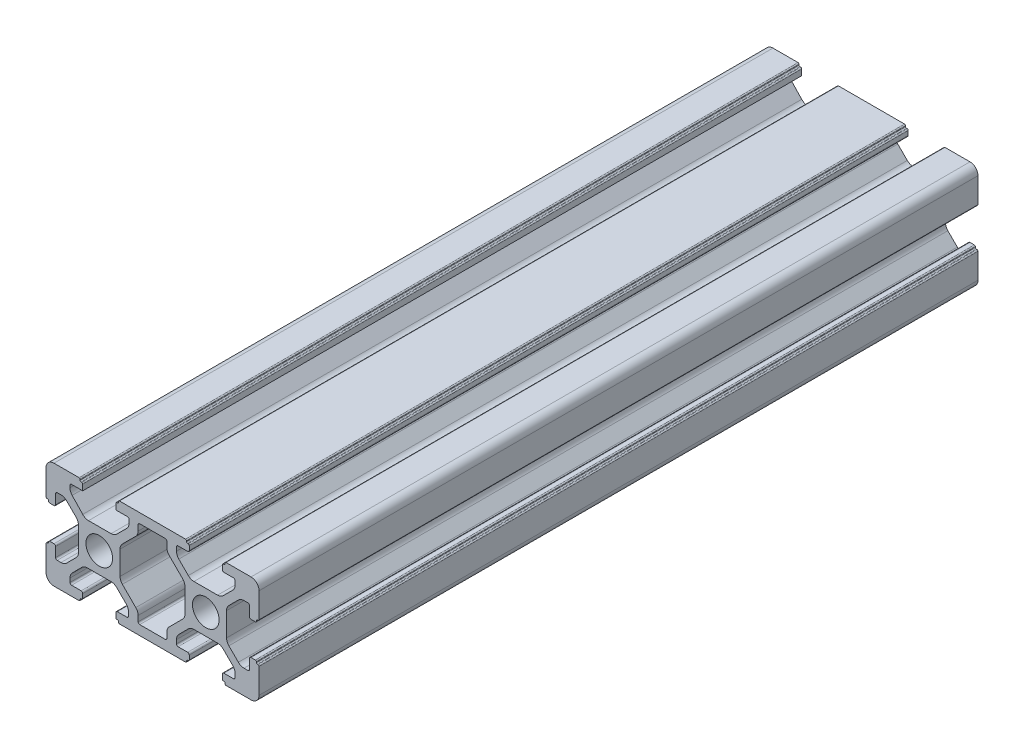
SolidWorks part; units mm, degrees
material "6063-O"
ref_plane "Front Plane" through (0, 0, 0) normal (0, 0, 1) x (1, 0, 0)
ref_plane "Top Plane" through (0, 0, 0) normal (0, 1, 0) x (1, 0, 0)
ref_plane "Right Plane" through (0, 0, 0) normal (1, 0, 0) x (0, 0, -1)
sketch "Sketch1" plane through (0, 0, 0) normal (0, 0, 1) x (1, 0, 0)
  line L0 (1.5, 0) -> (6.2, 0)
  line L1 (40, 1.5) -> (40, 6.2)
  line L2 (38.5, 20) -> (33.8, 20)
  line L3 (0, 18.5) -> (0, 13.8)
  line L4 (17.6, 1.8) -> (22.4, 1.8)
  line L5 (32.218, 13.9) -> (27.782, 13.9)
  line L6 (26.1, 12.218) -> (26.1, 7.782)
  line L7 (17.6, 18.2) -> (22.4, 18.2)
  line L8 (12.218, 13.9) -> (7.9864, 13.9)
  line L9 (6.1, 12.218) -> (6.1, 7.782)
  line L10 (7.782, 6.1) -> (12.218, 6.1)
  line L11 (13.9, 7.782) -> (13.9, 12.218)
  line L12 (27.782, 6.1) -> (32.218, 6.1)
  line L13 (33.9, 7.782) -> (33.9, 12.218)
  line L14 (26.7213, 14.3393) -> (24.9393, 16.1213)
  line L15 (33.2787, 14.3393) -> (35.0607, 16.1213)
  line L16 (34.3393, 13.2787) -> (36.1213, 15.0607)
  line L17 (25.6607, 6.7213) -> (23.1393, 4.2)
  line L18 (15.2, 1.8) -> (13.4, 1.8)
  line L19 (26.7213, 5.6607) -> (24.9393, 3.8787)
  line L20 (24.8, 1.8) -> (26.6, 1.8)
  line L21 (15.3, 18.2) -> (13.1, 18.2)
  line L22 (13.2787, 14.3393) -> (15.1607, 16.2213)
  line L23 (14.3393, 13.2787) -> (16.8607, 15.8)
  line L24 (5.6607, 6.7213) -> (3.8787, 4.9393)
  line L25 (6.7213, 5.6607) -> (4.9393, 3.8787)
  line L26 (6.897, 14.3689) -> (4.9106, 16.4674)
  line L27 (5.6607, 13.2787) -> (3.8787, 15.0607)
  line L28 (14.3393, 6.7213) -> (16.8607, 4.2)
  line L29 (13.2787, 5.6607) -> (15.0607, 3.8787)
  line L30 (24.8, 18.2) -> (26.6, 18.2)
  line L31 (25.6607, 13.2787) -> (23.1393, 15.8)
  line L32 (34.3393, 6.7213) -> (36.1213, 4.9393)
  line L33 (33.2787, 5.6607) -> (35.0607, 3.8787)
  line L34 (1.8, 15.2) -> (1.8, 13.4)
  line L35 (24.5, 2.1) -> (24.5, 2.818)
  line L36 (4.5, 2.1) -> (4.5, 2.818)
  line L37 (2.818, 4.5) -> (2.1, 4.5)
  line L38 (4.5, 17.9) -> (4.5, 17.4986)
  line L39 (2.818, 15.5) -> (2.1, 15.5)
  line L40 (15.6, 17.9) -> (15.6, 17.282)
  line L41 (15.5, 2.818) -> (15.5, 2.1)
  line L42 (38.2, 15.2) -> (38.2, 13.4)
  line L43 (35.5, 2.818) -> (35.5, 2.1)
  line L44 (37.182, 4.5) -> (37.9, 4.5)
  line L45 (35.5, 17.182) -> (35.5, 17.9)
  line L46 (37.182, 15.5) -> (37.9, 15.5)
  line L47 (17.3, 2.1) -> (17.3, 3.1393)
  line L48 (22.7, 2.1) -> (22.7, 3.1393)
  line L49 (17.3, 17.9) -> (17.3, 16.8607)
  line L50 (22.7, 17.9) -> (22.7, 16.8607)
  line L51 (24.5, 17.9) -> (24.5, 17.182)
  line L52 (6.9, 19.3) -> (6.9, 18.2)
  line L53 (13.1, 19.3) -> (13.1, 18.2)
  line L54 (6.9, 1.5) -> (6.9, 0.7)
  line L55 (13.1, 1.5) -> (13.1, 0.7)
  line L56 (13.8, 0) -> (26.2, 0)
  line L57 (6.6, 1.8) -> (4.8, 1.8)
  line L58 (6.9, 18.2) -> (4.8, 18.2)
  line L59 (6.2, 20) -> (1.5, 20)
  line L60 (39.3, 6.9) -> (38.5, 6.9)
  line L61 (39.3, 13.1) -> (38.5, 13.1)
  line L62 (1.5, 13.1) -> (0.7, 13.1)
  line L63 (1.5, 6.9) -> (0.7, 6.9)
  line L64 (0, 6.2) -> (0, 1.5)
  line L65 (1.8, 6.6) -> (1.8, 4.8)
  line L66 (38.2, 6.6) -> (38.2, 4.8)
  line L67 (40, 13.8) -> (40, 18.5)
  line L68 (33.1, 19.3) -> (33.1, 18.5)
  line L69 (26.9, 19.3) -> (26.9, 18.5)
  line L70 (26.9, 1.5) -> (26.9, 0.7)
  line L71 (33.1, 1.5) -> (33.1, 0.7)
  line L72 (33.8, 0) -> (38.5, 0)
  line L73 (33.4, 1.8) -> (35.2, 1.8)
  line L74 (26.2, 20) -> (13.8, 20)
  line L75 (33.4, 18.2) -> (35.2, 18.2)
  line L76 (6.7, 0.5) -> (6.6, 0.5)
  line L77 (6.4, 0.3) -> (6.4, 0.2)
  line L78 (13.3, 0.5) -> (13.4, 0.5)
  line L79 (13.6, 0.3) -> (13.6, 0.2)
  line L80 (26.7, 0.5) -> (26.6, 0.5)
  line L81 (26.4, 0.3) -> (26.4, 0.2)
  line L82 (33.3, 0.5) -> (33.4, 0.5)
  line L83 (33.6, 0.3) -> (33.6, 0.2)
  line L85 (6.4, 19.8) -> (6.4, 19.7)
  line L86 (6.6, 19.5) -> (6.7, 19.5)
  line L87 (13.6, 19.8) -> (13.6, 19.7)
  line L88 (13.4, 19.5) -> (13.3, 19.5)
  line L89 (26.4, 19.8) -> (26.4, 19.7)
  line L90 (26.6, 19.5) -> (26.7, 19.5)
  line L91 (33.6, 19.8) -> (33.6, 19.7)
  line L92 (33.4, 19.5) -> (33.3, 19.5)
  line L93 (0.5, 13.3) -> (0.5, 13.4)
  line L94 (0.3, 13.6) -> (0.2, 13.6)
  line L95 (0.5, 6.7) -> (0.5, 6.6)
  line L96 (0.3, 6.4) -> (0.2, 6.4)
  line L97 (39.5, 13.3) -> (39.5, 13.4)
  line L98 (39.7, 13.6) -> (39.8, 13.6)
  line L99 (39.5, 6.7) -> (39.5, 6.6)
  line L100 (39.7, 6.4) -> (39.8, 6.4)
  circle A0 centre (10, 10) radius 2.5
  circle A1 centre (30, 10) radius 2.5
  arc A2 (38.5, 0) -> (40, 1.5) centre (38.5, 1.5) ccw
  arc A3 (40, 18.5) -> (38.5, 20) centre (38.5, 18.5) ccw
  arc A4 (1.5, 0) -> (0, 1.5) centre (1.5, 1.5) cw
  arc A5 (1.5, 20) -> (0, 18.5) centre (1.5, 18.5) ccw
  arc A6 (26.7213, 5.6607) -> (27.782, 6.1) centre (27.782, 4.6) cw
  arc A7 (32.218, 6.1) -> (33.2787, 5.6607) centre (32.218, 4.6) cw
  arc A8 (33.9, 7.782) -> (34.3393, 6.7213) centre (35.4, 7.782) ccw
  arc A9 (33.2787, 14.3393) -> (32.218, 13.9) centre (32.218, 15.4) cw
  arc A10 (14.3393, 6.7213) -> (13.9, 7.782) centre (15.4, 7.782) cw
  arc A11 (14.3393, 13.2787) -> (13.9, 12.218) centre (15.4, 12.218) ccw
  arc A12 (25.6607, 6.7213) -> (26.1, 7.782) centre (24.6, 7.782) ccw
  arc A13 (26.1, 12.218) -> (25.6607, 13.2787) centre (24.6, 12.218) ccw
  arc A14 (27.782, 13.9) -> (26.7213, 14.3393) centre (27.782, 15.4) cw
  arc A15 (5.6607, 13.2787) -> (6.1, 12.218) centre (4.6, 12.218) cw
  arc A16 (5.6607, 6.7213) -> (6.1, 7.782) centre (4.6, 7.782) ccw
  arc A17 (13.2787, 5.6607) -> (12.218, 6.1) centre (12.218, 4.6) ccw
  arc A18 (6.7213, 5.6607) -> (7.782, 6.1) centre (7.782, 4.6) cw
  arc A19 (13.2787, 14.3393) -> (12.218, 13.9) centre (12.218, 15.4) cw
  arc A20 (6.897, 14.3689) -> (7.9864, 13.9) centre (7.9864, 15.4) ccw
  arc A21 (36.1213, 4.9393) -> (37.182, 4.5) centre (37.182, 6) ccw
  arc A22 (36.1213, 15.0607) -> (37.182, 15.5) centre (37.182, 14) cw
  arc A23 (35.0607, 16.1213) -> (35.5, 17.182) centre (34, 17.182) ccw
  arc A24 (24.5, 17.182) -> (24.9393, 16.1213) centre (26, 17.182) ccw
  arc A25 (22.7, 16.8607) -> (23.1393, 15.8) centre (24.2, 16.8607) ccw
  arc A26 (17.3, 16.8607) -> (16.8607, 15.8) centre (15.8, 16.8607) cw
  arc A27 (4.9106, 16.4674) -> (4.5, 17.4986) centre (6, 17.4986) cw
  arc A28 (15.6, 17.282) -> (15.1607, 16.2213) centre (14.1, 17.282) cw
  arc A29 (3.8787, 15.0607) -> (2.818, 15.5) centre (2.818, 14) ccw
  arc A30 (3.8787, 4.9393) -> (2.818, 4.5) centre (2.818, 6) cw
  arc A31 (4.9393, 3.8787) -> (4.5, 2.818) centre (6, 2.818) ccw
  arc A32 (35.0607, 3.8787) -> (35.5, 2.818) centre (34, 2.818) cw
  arc A33 (24.9393, 3.8787) -> (24.5, 2.818) centre (26, 2.818) ccw
  arc A34 (22.7, 3.1393) -> (23.1393, 4.2) centre (24.2, 3.1393) cw
  arc A35 (17.3, 3.1393) -> (16.8607, 4.2) centre (15.8, 3.1393) ccw
  arc A36 (15.5, 2.818) -> (15.0607, 3.8787) centre (14, 2.818) ccw
  arc A37 (1.8, 6.6) -> (1.5, 6.9) centre (1.5, 6.6) ccw
  arc A38 (1.8, 13.4) -> (1.5, 13.1) centre (1.5, 13.4) cw
  arc A39 (17.6, 18.2) -> (17.3, 17.9) centre (17.6, 17.9) ccw
  arc A40 (22.4, 1.8) -> (22.7, 2.1) centre (22.4, 2.1) ccw
  arc A41 (17.6, 1.8) -> (17.3, 2.1) centre (17.6, 2.1) cw
  arc A42 (15.2, 1.8) -> (15.5, 2.1) centre (15.2, 2.1) ccw
  arc A43 (6.6, 1.8) -> (6.9, 1.5) centre (6.6, 1.5) cw
  arc A44 (13.4, 1.8) -> (13.1, 1.5) centre (13.4, 1.5) ccw
  arc A45 (24.8, 1.8) -> (24.5, 2.1) centre (24.8, 2.1) cw
  arc A46 (35.2, 1.8) -> (35.5, 2.1) centre (35.2, 2.1) ccw
  arc A47 (26.6, 1.8) -> (26.9, 1.5) centre (26.6, 1.5) cw
  arc A48 (33.4, 1.8) -> (33.1, 1.5) centre (33.4, 1.5) ccw
  arc A49 (26.9, 18.5) -> (26.6, 18.2) centre (26.6, 18.5) cw
  arc A50 (33.1, 18.5) -> (33.4, 18.2) centre (33.4, 18.5) ccw
  arc A51 (37.9, 4.5) -> (38.2, 4.8) centre (37.9, 4.8) ccw
  arc A52 (38.5, 13.1) -> (38.2, 13.4) centre (38.5, 13.4) cw
  arc A53 (38.5, 6.9) -> (38.2, 6.6) centre (38.5, 6.6) ccw
  arc A54 (38.2, 15.2) -> (37.9, 15.5) centre (37.9, 15.2) ccw
  arc A55 (35.2, 18.2) -> (35.5, 17.9) centre (35.2, 17.9) cw
  arc A56 (24.8, 18.2) -> (24.5, 17.9) centre (24.8, 17.9) ccw
  arc A57 (22.4, 18.2) -> (22.7, 17.9) centre (22.4, 17.9) cw
  arc A58 (15.3, 18.2) -> (15.6, 17.9) centre (15.3, 17.9) cw
  arc A59 (4.5, 17.9) -> (4.8, 18.2) centre (4.8, 17.9) cw
  arc A60 (1.8, 15.2) -> (2.1, 15.5) centre (2.1, 15.2) cw
  arc A61 (1.8, 4.8) -> (2.1, 4.5) centre (2.1, 4.8) ccw
  arc A62 (4.5, 2.1) -> (4.8, 1.8) centre (4.8, 2.1) ccw
  arc A63 (34.3393, 13.2787) -> (33.9, 12.218) centre (35.4, 12.218) ccw
  arc A64 (6.4, 0.2) -> (6.2, 0) centre (6.2, 0.2) cw
  arc A65 (6.6, 0.5) -> (6.4, 0.3) centre (6.6, 0.3) ccw
  arc A66 (6.7, 0.5) -> (6.9, 0.7) centre (6.7, 0.7) ccw
  arc A67 (13.6, 0.2) -> (13.8, 0) centre (13.8, 0.2) ccw
  arc A68 (13.4, 0.5) -> (13.6, 0.3) centre (13.4, 0.3) cw
  arc A69 (13.3, 0.5) -> (13.1, 0.7) centre (13.3, 0.7) cw
  arc A70 (26.4, 0.2) -> (26.2, 0) centre (26.2, 0.2) cw
  arc A71 (26.6, 0.5) -> (26.4, 0.3) centre (26.6, 0.3) ccw
  arc A72 (26.7, 0.5) -> (26.9, 0.7) centre (26.7, 0.7) ccw
  arc A73 (33.6, 0.2) -> (33.8, 0) centre (33.8, 0.2) ccw
  arc A74 (33.4, 0.5) -> (33.6, 0.3) centre (33.4, 0.3) cw
  arc A75 (33.3, 0.5) -> (33.1, 0.7) centre (33.3, 0.7) cw
  arc A76 (39.8, 6.4) -> (40, 6.2) centre (39.8, 6.2) cw
  arc A77 (39.5, 6.6) -> (39.7, 6.4) centre (39.7, 6.6) ccw
  arc A78 (39.5, 6.7) -> (39.3, 6.9) centre (39.3, 6.7) ccw
  arc A79 (39.5, 13.3) -> (39.3, 13.1) centre (39.3, 13.3) cw
  arc A80 (39.5, 13.4) -> (39.7, 13.6) centre (39.7, 13.4) cw
  arc A81 (39.8, 13.6) -> (40, 13.8) centre (39.8, 13.8) ccw
  arc A82 (33.3, 19.5) -> (33.1, 19.3) centre (33.3, 19.3) ccw
  arc A83 (33.6, 19.7) -> (33.4, 19.5) centre (33.4, 19.7) cw
  arc A84 (33.6, 19.8) -> (33.8, 20) centre (33.8, 19.8) cw
  arc A85 (26.7, 19.5) -> (26.9, 19.3) centre (26.7, 19.3) cw
  arc A86 (26.4, 19.7) -> (26.6, 19.5) centre (26.6, 19.7) ccw
  arc A87 (26.4, 19.8) -> (26.2, 20) centre (26.2, 19.8) ccw
  arc A88 (0.2, 6.4) -> (0, 6.2) centre (0.2, 6.2) ccw
  arc A89 (0.5, 6.6) -> (0.3, 6.4) centre (0.3, 6.6) cw
  arc A90 (0.5, 6.7) -> (0.7, 6.9) centre (0.7, 6.7) cw
  arc A91 (13.3, 19.5) -> (13.1, 19.3) centre (13.3, 19.3) ccw
  arc A92 (13.6, 19.7) -> (13.4, 19.5) centre (13.4, 19.7) cw
  arc A93 (13.6, 19.8) -> (13.8, 20) centre (13.8, 19.8) cw
  arc A94 (6.2, 20) -> (6.4, 19.8) centre (6.2, 19.8) cw
  arc A95 (6.7, 19.5) -> (6.9, 19.3) centre (6.7, 19.3) cw
  arc A96 (6.4, 19.7) -> (6.6, 19.5) centre (6.6, 19.7) ccw
  arc A97 (0.5, 13.3) -> (0.7, 13.1) centre (0.7, 13.3) ccw
  arc A98 (0.2, 13.6) -> (0, 13.8) centre (0.2, 13.8) cw
  arc A99 (0.5, 13.4) -> (0.3, 13.6) centre (0.3, 13.4) ccw
  point P87 (0, 0)
  point P178 (1.8, 6.9)
  point P181 (1.8, 13.1)
  point P186 (22.7, 1.8)
  point P193 (6.9, 1.8)
  point P204 (33.1, 1.8)
  point P209 (33.1, 18.2)
  point P216 (38.2, 6.9)
  point P243 (6.9, 0.5)
  point P248 (13.6, 0.5)
  point P257 (26.9, 0.5)
extrude "Boss-Extrude2" add sketch "Sketch1" along normal blind 135 contours A57 L7 A39 L49 A26 L23 A11 L11 A10 L28 A35 L47 A41 L4 A40 L48 A34 L17 A12 L6 A13 L31 A25 L50 | A0 | A1 | L59 A5 L3 A98 L94 A99 L93 A97 L62 A38 L34 A60 L39 A29 L27 A15 L9 A16 L24 A30 L37 A61 L65 A37 L63 A90 L95 A89 L96 A88 L64 A4 L0 A64 L77 A65 L76 A66 L54 A43 L57 A62 L36 A31 L25 A18 L10 A17 L29 A36 L41 A42 L18 A44 L55 A69 L78 A68 L79 A67 L56 A70 L81 A71 L80 A72 L70 A47 L20 A45 L35 A33 L19 A6 L12 A7 L33 A32 L43 A46 L73 A48 L71 A75 L82 A74 L83 A73 L72 A2 L1 A76 L100 A77 L99 A78 L60 A53 L66 A51 L44 A21 L32 A8 L13 A63 L16 A22 L46 A54 L42 A52 L61 A79 L97 A80 L98 A81 L67 A3 L2 A84 L91 A83 L92 A82 L68 A50 L75 A55 L45 A23 L15 A9 L5 A14 L14 A24 L51 A56 L30 A49 L69 A85 L90 A86 L89 A87 L74 A93 L87 A92 L88 A91 L53 L21 A58 L40 A28 L22 A19 L8 A20 L26 A27 L38 A59 L58 L52 A95 L86 A96 L85 A94
